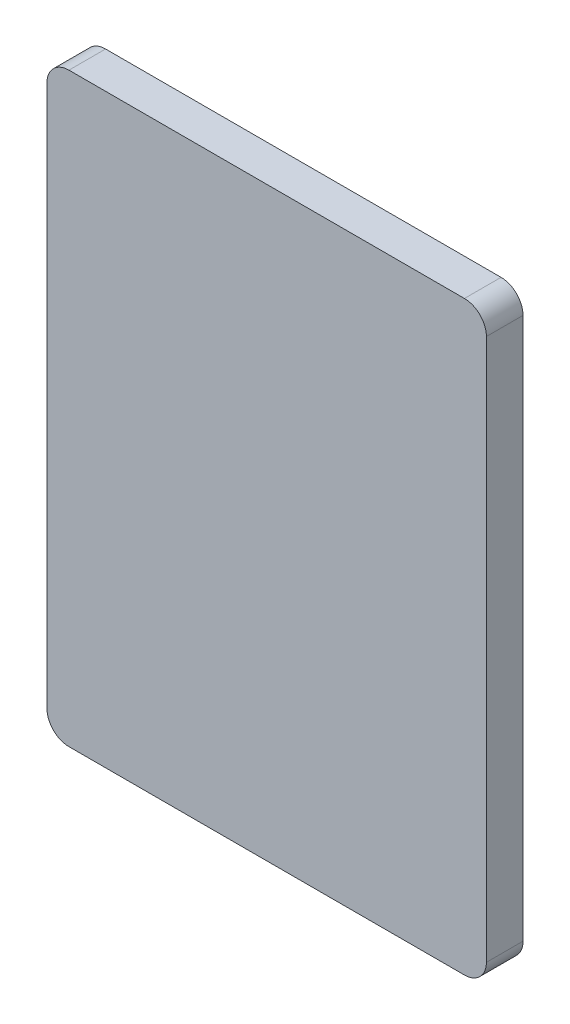
SolidWorks part; units mm, degrees
material "ABS"
ref_plane "Спереди" through (0, 0, 0) normal (0, 0, 1) x (1, 0, 0)
ref_plane "Сверху" through (0, 0, 0) normal (0, 1, 0) x (1, 0, 0)
ref_plane "Справа" through (0, 0, 0) normal (1, 0, 0) x (0, 0, -1)
sketch "Эскиз1" plane through (0, 0, 0) normal (0, 0, 1) x (1, 0, 0)
  line L1 (30, -40) -> (-30, -40)
  line L2 (30, -40) -> (30, 40)
  line L3 (30, 40) -> (-30, 40)
  line L4 (-30, -40) -> (-30, 40)
  line L5 (30, -40) -> (-30, 40) construction
  line L6 (30, 40) -> (-30, -40) construction
  point P0 (0, 0)
  dimension "D1" = 60
  dimension "D2" = 80
extrude "Бобышка-Вытянуть1" add sketch "Эскиз1" along normal blind 5
fillet "Скругление1" radius 3 4 edges at (30, -40, 2.5) (-30, -40, 2.5) (-30, 40, 2.5) (30, 40, 2.5)
